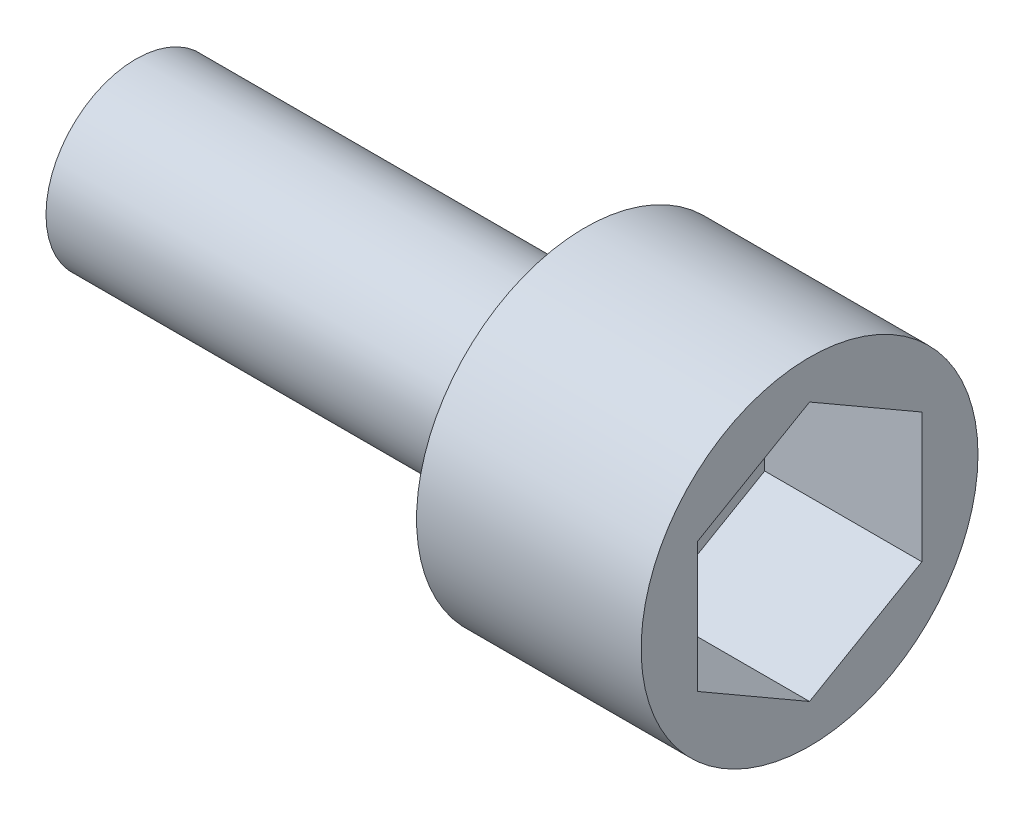
SolidWorks part; units mm, degrees
ref_plane "Front Plane" through (0, 0, 0) normal (1, 0, 0) x (0, 1, 0)
ref_plane "Top Plane" through (0, 0, 0) normal (0, 0, 1) x (0, 1, 0)
ref_plane "Right Plane" through (0, 0, 0) normal (0, 1, 0) x (-1, 0, 0)
sketch "Sketch1" plane through (0, 0, 0) normal (1, 0, 0) x (0, 1, 0)
  circle A0 centre (0, 0) radius 7.5
  dimension "D1" = 15
extrude "Boss-Extrude1" add sketch "Sketch1" along normal blind 10
sketch "Sketch2" plane through (10, 0, 0) normal (1, 0, 0) x (0, 1, 0)
  line L1 (5.7735, 0) -> (2.8868, 5)
  line L2 (2.8868, 5) -> (-2.8868, 5)
  line L3 (-2.8868, 5) -> (-5.7735, 0)
  line L4 (-5.7735, 0) -> (-2.8868, -5)
  line L5 (-2.8868, -5) -> (2.8868, -5)
  line L6 (2.8868, -5) -> (5.7735, 0)
  circle A0 centre (0, 0) radius 5 construction
  dimension "D1" = 10
extrude "Cut-Extrude1" cut sketch "Sketch2" against normal blind 7
sketch "Sketch3" plane through (0, 0, 0) normal (-1, 0, 0) x (0, -1, 0)
  circle A0 centre (0, 0) radius 4
  dimension "D1" = 8
extrude "Boss-Extrude2" add sketch "Sketch3" along normal blind 20
